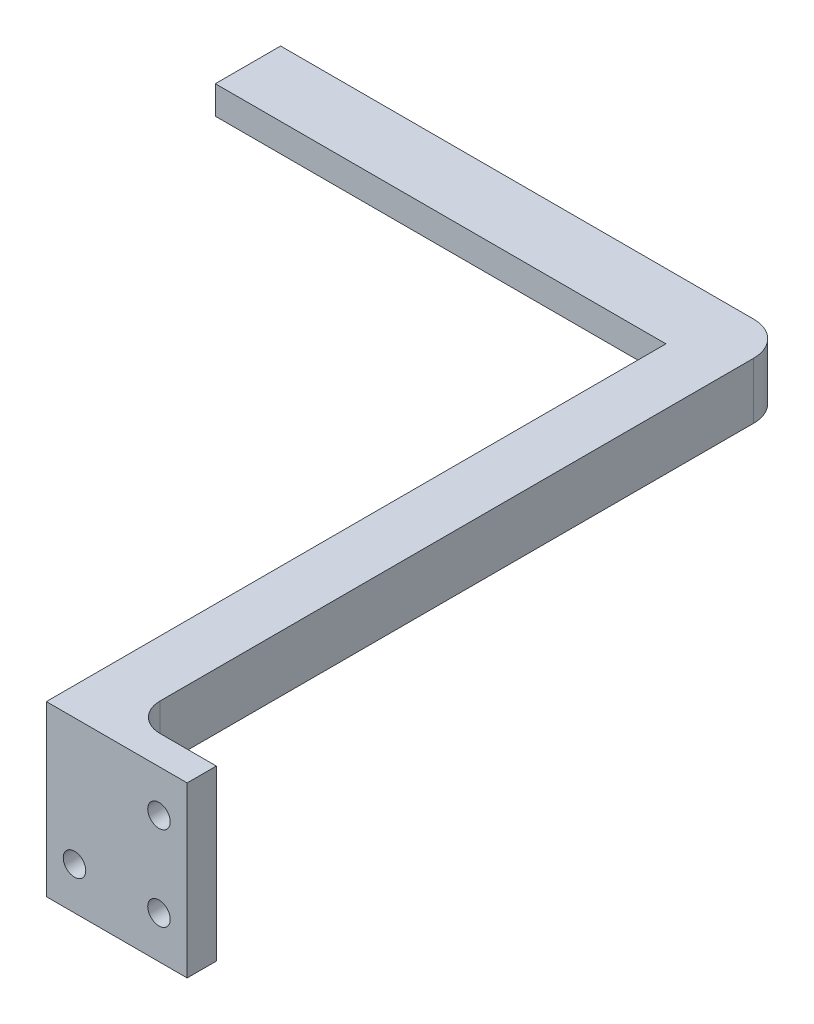
SolidWorks part; units mm, degrees
ref_plane "Front Plane" through (0, 0, 0) normal (0, 0, 1) x (1, 0, 0)
ref_plane "Top Plane" through (0, 0, 0) normal (0, 1, 0) x (1, 0, 0)
ref_plane "Right Plane" through (0, 0, 0) normal (1, 0, 0) x (0, 0, -1)
sketch "Sketch1" plane through (0, 0, 0) normal (0, 1, 0) x (1, 0, 0)
  line L0 (0, 0) -> (0, 110)
  line L2 (0, 110) -> (-10, 110)
  line L3 (0, 110) -> (0, 0)
  line L4 (0, 0) -> (-10, 0)
  line L5 (-10, 110) -> (-10, 0)
  line L6 (0, 110) -> (-90, 110)
  line L7 (0, 110) -> (0, 121.5906)
  line L8 (0, 121.5906) -> (-90, 121.5906)
  line L9 (-90, 110) -> (-90, 121.5906)
  line L10 (0, 0) -> (15, 0)
  line L11 (0, 0) -> (0, 7.1827)
  line L12 (0, 7.1827) -> (15, 7.1827)
  line L13 (15, 0) -> (15, 7.1827)
extrude "Boss-Extrude1" add sketch "Sketch1" along normal blind 10 contours L9 L6 L2 L7 L8 | L2 L5 L4 L0 L3 | L10 L13 L12 L0
sketch "Sketch2" plane through (0, 0, 0) normal (0, -1, 0) x (1, 0, 0)
  line L0 (-10, -110) -> (-10, 0) construction
  line L1 (15, 0) -> (-10, 0)
  line L2 (15, 0) -> (15, -7.1827)
  line L3 (15, -7.1827) -> (-10, -7.1827)
  line L4 (-10, 0) -> (-10, -7.1827)
extrude "Boss-Extrude2" add sketch "Sketch2" along normal blind 20
sketch "Sketch3" plane through (0, 0, -7.1827) normal (0, 0, -1) x (-1, 0, 0)
  line L0 (10, -20) -> (-15, -20) construction
  line L1 (-15, 10) -> (-10, 10)
  line L2 (-15, 10) -> (-15, -20)
  line L3 (-15, -20) -> (-10, -20)
  line L4 (-10, 10) -> (-10, -20)
  line L5 (-15, -5) -> (-10, -5)
  line L6 (-10, -5) -> (-10, 10)
  line L7 (-2.5, -20) -> (-2.5, -11.4632)
  circle A0 centre (-10, 2.5) radius 2
  circle A1 centre (-10, -12.5) radius 2
  circle A2 centre (5, -12.5) radius 2
extrude "Cut-Extrude1" cut sketch "Sketch3" against normal blind 20 contours A0 | A1 | A2
sketch "Sketch4" plane through (0, 0, -7.1827) normal (0, 0, -1) x (-1, 0, 0)
  line L6 (10, 0) -> (0, 0)
  line L7 (10, 0) -> (0, 0)
  line L8 (0, 10) -> (-15, 10)
  line L9 (-15, 10) -> (-15, -20)
  line L10 (-15, -20) -> (10, -20)
  line L11 (10, -20) -> (10, 0)
  line L14 (0, 10) -> (-15, 10)
  line L15 (-15, 10) -> (-15, -20)
  line L16 (-15, -20) -> (10, -20)
  line L17 (10, -20) -> (10, 0)
  line L18 (0, 0) -> (0, 10)
  line L19 (0, 0) -> (0, 10)
  circle A1 centre (5, -12.5) radius 2
  circle A2 centre (5, -12.5) radius 2
  circle A3 centre (-10, -12.5) radius 2
  circle A4 centre (-10, -12.5) radius 2
  circle A5 centre (-10, 2.5) radius 2
  circle A6 centre (-10, 2.5) radius 2
  dimension "D1" = 0
  dimension "D2" = 0
  dimension "D3" = 0
  dimension "D4" = 0
extrude "Cut-Extrude2" cut sketch "Sketch4" against normal blind 2
fillet "Fillet2" radius 5 2 edges at (0, 5, -5.1827) (-5, 0, -5.1827)
chamfer "Chamfer2" distance 5 angle 45 1 edges at (-50, 0, -110)
fillet "Fillet3" radius 6 1 edges at (0, 5, -121.5906)
